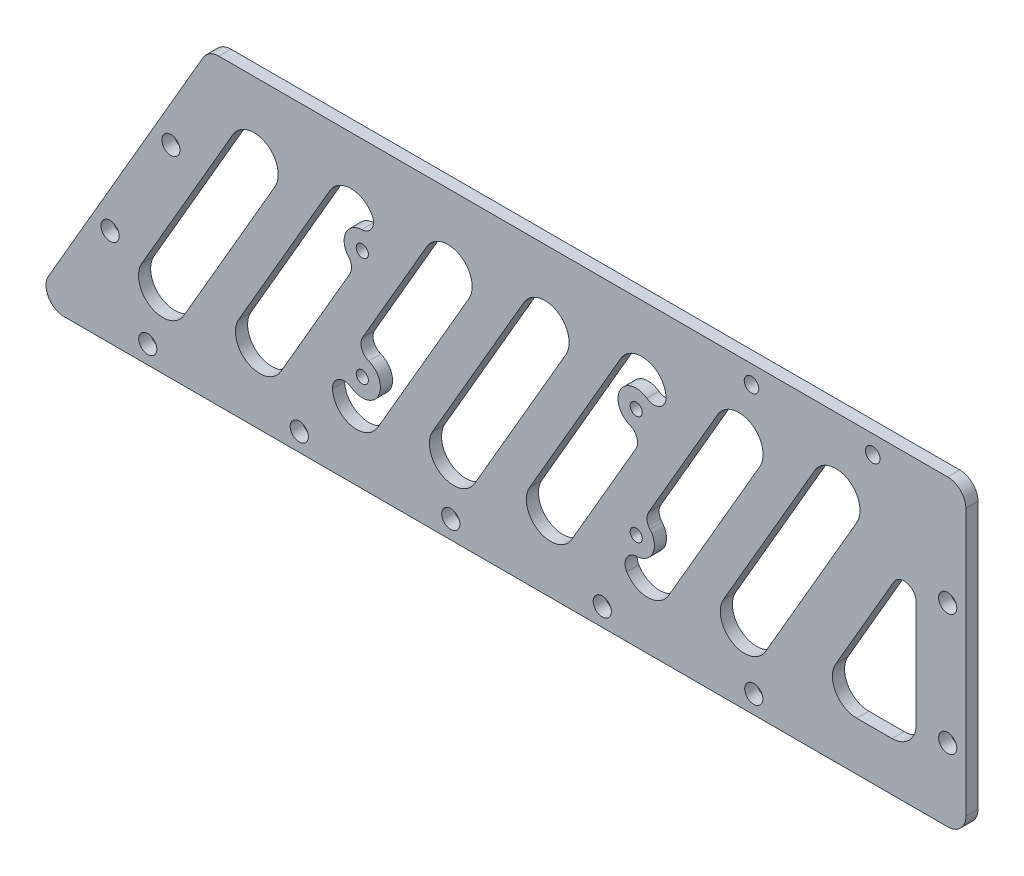
SolidWorks part; units mm, degrees
material "Thornel Mat VMA"
ref_plane "前视基准面" through (0, 0, 0) normal (0, 0, 1) x (1, 0, 0)
ref_plane "上视基准面" through (0, 0, 0) normal (0, 1, 0) x (1, 0, 0)
ref_plane "右视基准面" through (0, 0, 0) normal (1, 0, 0) x (0, 0, -1)
sketch "草图1" plane through (0, 0, 0) normal (0, 0, 1) x (1, 0, 0)
  line L1 (77, -25) -> (-77, -25)
  line L2 (77, -25) -> (77, 25)
  line L3 (77, 25) -> (-77, 25)
  line L4 (-77, -25) -> (-77, 25)
  line L5 (77, -25) -> (-77, 25) construction
  line L6 (77, 25) -> (-77, -25) construction
  point P0 (0, 0)
  dimension "D1" = 154
  dimension "D2" = 50
extrude "凸台-拉伸1" add sketch "草图1" along normal blind 2
sketch "草图2" plane through (0, 0, 0) normal (0, 0, -1) x (-1, 0, 0)
  line L0 (0, 25) -> (0, -25) construction
  line L1 (-77, 25) -> (77, 25) construction
  line L2 (77, -25) -> (-77, -25) construction
  line L3 (-77, 0) -> (77, 0) construction
  line L4 (-77, -25) -> (-77, 25) construction
  line L5 (77, 25) -> (77, -25) construction
  circle A0 centre (22.6, 9) radius 1
  circle A1 centre (-22.6, 9) radius 1
  circle A2 centre (22.6, -9) radius 1
  circle A3 centre (-22.6, -9) radius 1
  dimension "D1" = 2
  dimension "D2" = 18
  dimension "D3" = 45.2
extrude "切除-拉伸1" cut sketch "草图2" against normal blind 10
sketch "草图3" plane through (0, 0, 2) normal (0, 0, 1) x (1, 0, 0)
  line L0 (-77, -25) -> (-48, 25)
  line L1 (77, 25) -> (-77, 25) construction
  line L2 (-77, 0) -> (77, 0) construction
  line L3 (-77, 25) -> (-77, -25) construction
  line L4 (77, -25) -> (77, 25) construction
  line L5 (0, 25) -> (0, -25) construction
  line L6 (-77, -25) -> (77, -25) construction
  line L7 (-48, 25) -> (-77, 25)
  line L8 (-77, 25) -> (-77, -25)
  dimension "D1" = 48
extrude "切除-拉伸2" cut sketch "草图3" against normal blind 10
sketch "草图4" plane through (0, 0, 0) normal (0, 0, -1) x (-1, 0, 0)
  line L0 (-77, -22) -> (75.26, -22) construction
  line L1 (-77, -25) -> (-77, 25) construction
  line L2 (77, -25) -> (48, 25) construction
  line L3 (77, -25) -> (-77, -25) construction
  circle A0 centre (-42, -22) radius 1.5
  circle A1 centre (-17, -22) radius 1.5
  circle A2 centre (8, -22) radius 1.5
  circle A3 centre (33, -22) radius 1.5
  circle A4 centre (58, -22) radius 1.5
  dimension "D3" = 3
  dimension "D4" = 35
  dimension "D2" = 3
  dimension "D1" = 5
extrude "切除-拉伸3" cut sketch "草图4" against normal blind 10
fillet "圆角1" radius 3 4 edges at (77, -25, 1) (77, 25, 1) (-48, 25, 1) (-77, -25, 1)
sketch "草图5" plane through (0, 0, 0) normal (0, 0, -1) x (-1, 0, 0)
  line L0 (7.5258, -12.9755) -> (-7.5258, 12.9755) construction
  line L1 (74.387, -20.4948) -> (48.867, 23.5052) construction
  line L2 (7.5258, -12.9755) -> (-7.5258, 12.9755) construction
  line L3 (4.0656, -14.9823) -> (-10.9859, 10.9686)
  line L4 (10.9859, -10.9686) -> (-4.0656, 14.9823)
  line L5 (-77, 0) -> (62.5, 0) construction
  line L6 (-77, -22) -> (-77, 22) construction
  line L7 (23.5258, -12.9755) -> (8.4742, 12.9755) construction
  line L8 (23.5258, -12.9755) -> (8.4742, 12.9755) construction
  line L9 (20.0656, -14.9823) -> (5.0141, 10.9686)
  line L10 (26.9859, -10.9686) -> (11.9344, 14.9823)
  line L11 (39.5258, -12.9755) -> (24.4742, 12.9755) construction
  line L12 (39.5258, -12.9755) -> (24.4742, 12.9755) construction
  line L13 (36.0656, -14.9823) -> (21.0141, 10.9686)
  line L14 (42.9859, -10.9686) -> (27.9344, 14.9823)
  line L15 (55.5258, -12.9755) -> (40.4742, 12.9755) construction
  line L16 (55.5258, -12.9755) -> (40.4742, 12.9755) construction
  line L17 (52.0656, -14.9823) -> (37.0141, 10.9686)
  line L18 (58.9859, -10.9686) -> (43.9344, 14.9823)
  line L19 (-8.4742, -12.9755) -> (-23.5258, 12.9755) construction
  line L20 (-11.9344, -14.9823) -> (-26.9859, 10.9686)
  line L21 (-5.0141, -10.9686) -> (-20.0656, 14.9823)
  line L22 (-24.4742, -12.9755) -> (-39.5258, 12.9755) construction
  line L23 (-27.9344, -14.9823) -> (-42.9859, 10.9686)
  line L24 (-21.0141, -10.9686) -> (-36.0656, 14.9823)
  line L25 (-40.4742, -12.9755) -> (-55.5258, 12.9755) construction
  line L26 (-43.9344, -14.9823) -> (-58.9859, 10.9686)
  line L27 (-37.0141, -10.9686) -> (-52.0656, 14.9823)
  arc A0 (4.0656, -14.9823) -> (10.9859, -10.9686) centre (7.5258, -12.9755) ccw
  arc A1 (-4.0656, 14.9823) -> (-10.9859, 10.9686) centre (-7.5258, 12.9755) ccw
  arc A2 (20.0656, -14.9823) -> (26.9859, -10.9686) centre (23.5258, -12.9755) ccw
  arc A3 (11.9344, 14.9823) -> (5.0141, 10.9686) centre (8.4742, 12.9755) ccw
  arc A4 (36.0656, -14.9823) -> (42.9859, -10.9686) centre (39.5258, -12.9755) ccw
  arc A5 (27.9344, 14.9823) -> (21.0141, 10.9686) centre (24.4742, 12.9755) ccw
  arc A6 (52.0656, -14.9823) -> (58.9859, -10.9686) centre (55.5258, -12.9755) ccw
  arc A7 (43.9344, 14.9823) -> (37.0141, 10.9686) centre (40.4742, 12.9755) ccw
  arc A8 (-11.9344, -14.9823) -> (-5.0141, -10.9686) centre (-8.4742, -12.9755) ccw
  arc A9 (-20.0656, 14.9823) -> (-26.9859, 10.9686) centre (-23.5258, 12.9755) ccw
  arc A10 (-27.9344, -14.9823) -> (-21.0141, -10.9686) centre (-24.4742, -12.9755) ccw
  arc A11 (-36.0656, 14.9823) -> (-42.9859, 10.9686) centre (-39.5258, 12.9755) ccw
  arc A12 (-43.9344, -14.9823) -> (-37.0141, -10.9686) centre (-40.4742, -12.9755) ccw
  arc A13 (-52.0656, 14.9823) -> (-58.9859, 10.9686) centre (-55.5258, 12.9755) ccw
  point P4 (0, 0)
  point P6 (0, 0)
  point P19 (16, 0)
  point P21 (16, 0)
  point P27 (32, 0)
  point P29 (32, 0)
  point P35 (48, 0)
  point P37 (48, 0)
  point P42 (-16, 0)
  point P49 (-32, 0)
  point P56 (-48, 0)
  dimension "D2" = 4
  dimension "D1" = 30
  dimension "D3" = 4
  dimension "D4" = 4
extrude "切除-拉伸4" cut sketch "草图5" against normal blind 5
sketch "草图6" plane through (0, 0, 0) normal (0, 0, -1) x (-1, 0, 0)
  line L0 (0, 25) -> (0, -25) construction
  line L1 (-64.029, 0) -> (50.86, 0) construction
  line L2 (-77, 0) -> (77, 0) construction
  circle A0 centre (22.6, 9) radius 3
  circle A1 centre (22.6, -9) radius 3
  circle A2 centre (22.6, -9) radius 1
  circle A3 centre (22.6, 9) radius 1
  circle A7 centre (-22.6, 9) radius 1
  circle A8 centre (-22.6, -9) radius 1
  circle A9 centre (-22.6, -9) radius 3
  circle A10 centre (-22.6, 9) radius 3
  dimension "D1" = 6
  dimension "D2" = 6
extrude "凸台-拉伸2" add sketch "草图6" against normal blind 2
fillet "圆角2" radius 2 8 edges at (-20.7982, 11.3986, 1) (-23.7604, 6.2335, 1) (-24.4954, -6.6746, 1) (-25.5596, -8.5095, 1) (20.7982, -11.3986, 1) (23.7604, -6.2335, 1) (24.4954, 6.6746, 1) (25.5596, 8.5095, 1)
sketch "草图7" plane through (0, 0, 0) normal (0, 0, -1) x (-1, 0, 0)
  line L0 (-68.8095, 11.9607) -> (-52.0266, -16.9755)
  line L1 (-52.0266, -16.9755) -> (-68.8095, -16.9755)
  line L2 (-68.8095, -16.9755) -> (-68.8095, 11.9607)
  line L3 (-58.9859, 10.9686) -> (-43.9344, -14.9823) construction
  arc A0 (-43.9344, -14.9823) -> (-37.0141, -10.9686) centre (-40.4742, -12.9755) ccw construction
  dimension "D1" = 8
extrude "切除-拉伸5" cut sketch "草图7" against normal blind 5
fillet "圆角3" radius 4 2 edges at (68.8095, -16.9755, 1) (52.0266, -16.9755, 1)
fillet "圆角4" radius 2 1 edges at (68.8095, 11.9607, 1)
sketch "草图19" plane through (0, 0, 0) normal (0, 0, -1) x (-1, 0, 0)
  line L1 (-77, -22) -> (-77, 22) construction
  line L2 (71.7919, -25) -> (-74, -25) construction
  circle A2 centre (-74, -13) radius 1.5
  circle A3 centre (-74, 7) radius 1.5
  dimension "D1" = 3
  dimension "D2" = 3
  dimension "D3" = 20
  dimension "D4" = 3
  dimension "D5" = 12
extrude "切除-拉伸6" cut sketch "草图19" against normal blind 10
sketch "草图20" plane through (0, 0, 0) normal (0, 0, -1) x (-1, 0, 0)
  line L0 (74.387, -20.4948) -> (48.867, 23.5052) construction
  circle A0 centre (64.2193, -8.9438) radius 1.5
  circle A1 centre (54.185, 8.3568) radius 1.5
  dimension "D1" = 3
  dimension "D3" = 3
  dimension "D2" = 20
extrude "切除-拉伸7" cut sketch "草图20" against normal through all
sketch "草图22" plane through (0, 0, 0) normal (0, 0, -1) x (-1, 0, 0)
  circle A0 centre (-41.6255, 22) radius 1.2 construction
  circle A1 centre (-61.6255, 22) radius 1.2 construction
  circle A2 centre (-41.6255, 22) radius 1.2
  circle A3 centre (-61.6255, 22) radius 1.2
extrude "切除-拉伸9" cut sketch "草图22" against normal blind 10
